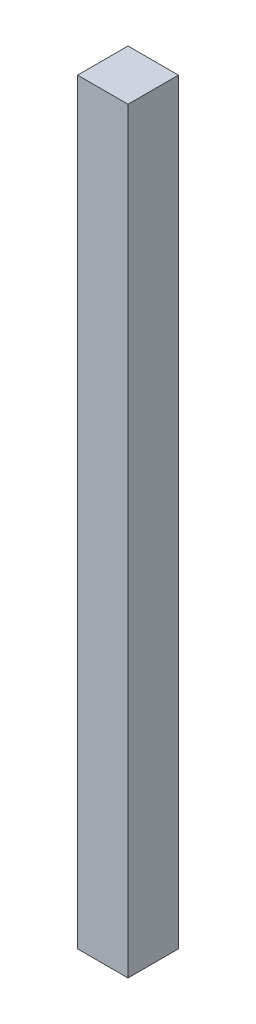
SolidWorks part; units mm, degrees
ref_plane "Alzado" through (0, 0, 0) normal (0, 0, 1) x (1, 0, 0)
ref_plane "Planta" through (0, 0, 0) normal (0, 1, 0) x (1, 0, 0)
ref_plane "Vista lateral" through (0, 0, 0) normal (1, 0, 0) x (0, 0, -1)
sketch "Sketch1" plane through (0, 0, 0) normal (0, 1, 0) x (1, 0, 0)
  line L1 (-10, -10) -> (10, -10)
  line L2 (-10, -10) -> (-10, 10)
  line L3 (-10, 10) -> (10, 10)
  line L4 (10, -10) -> (10, 10)
  line L5 (-10, -10) -> (10, 10) construction
  line L6 (-10, 10) -> (10, -10) construction
  point P0 (0, 0)
  dimension "D1" = 20
  dimension "D2" = 20
extrude "Boss-Extrude1" add sketch "Sketch1" along normal blind 300
